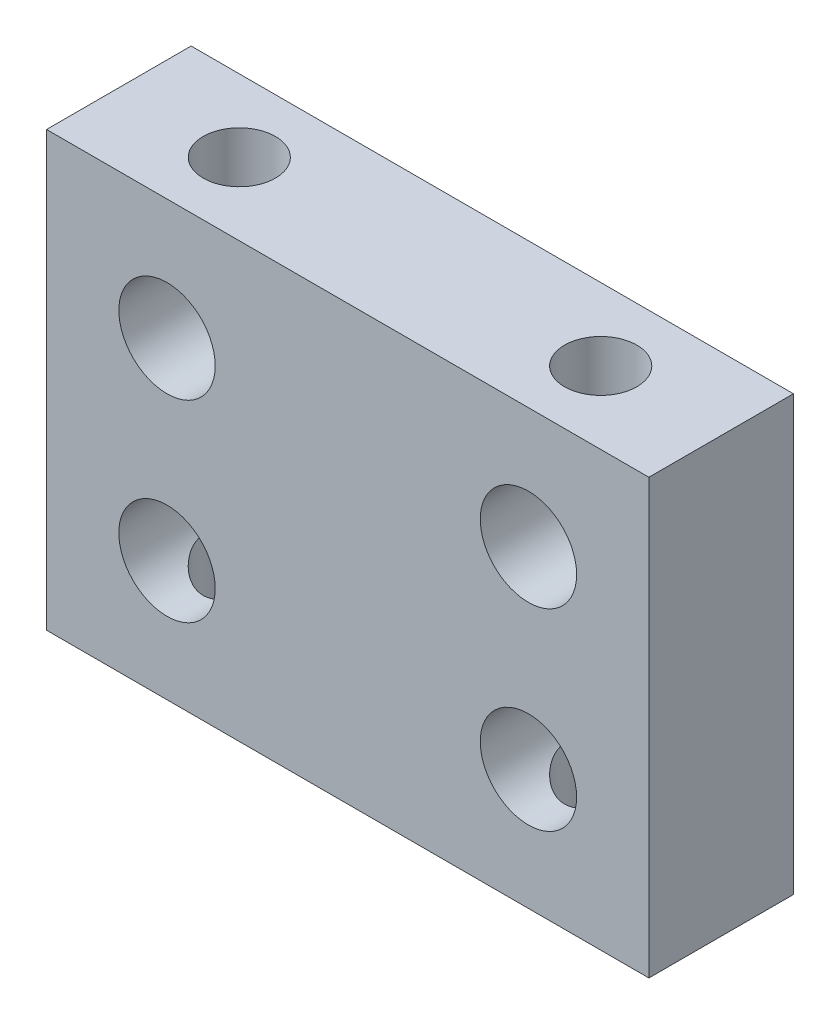
SolidWorks part; units mm, degrees
material "Beech"
ref_plane "Front Plane" through (0, 0, 0) normal (0, 0, 1) x (1, 0, 0)
ref_plane "Top Plane" through (0, 0, 0) normal (0, 1, 0) x (1, 0, 0)
ref_plane "Right Plane" through (0, 0, 0) normal (1, 0, 0) x (0, 0, -1)
sketch "Sketch1" plane through (0, 0, 0) normal (0, 0, 1) x (1, 0, 0)
  line L0 (-37.9574, 8) -> (34.5401, 8) construction
  line L1 (-25, -18) -> (25, -18)
  line L2 (-25, -18) -> (-25, 18)
  line L3 (-25, 18) -> (25, 18)
  line L4 (25, -18) -> (25, 18)
  line L5 (-25, -18) -> (25, 18) construction
  line L6 (-25, 18) -> (25, -18) construction
  line L7 (-37.9574, -8) -> (34.5401, -8) construction
  line L8 (-15, 21.2058) -> (-15, -23.6675) construction
  line L9 (15, 21.2058) -> (15, -23.6675) construction
  circle A0 centre (-15, 8) radius 4
  circle A1 centre (-15, -8) radius 4
  circle A2 centre (15, -8) radius 4
  circle A3 centre (15, 8) radius 4
  point P0 (0, 0)
  dimension "D7" = 8
  dimension "D8" = 8
  dimension "D9" = 8
  dimension "D10" = 8
  dimension "D1" = 50
  dimension "D2" = 36
  dimension "D3" = 10
  dimension "D4" = 10
  dimension "D5" = 15
  dimension "D6" = 15
extrude "Boss-Extrude1" add sketch "Sketch1" along normal blind 12
sketch "Sketch2" plane through (0, 18, 0) normal (0, 1, 0) x (1, 0, 0)
  line L0 (-22.806, -6) -> (31.3966, -6) construction
  line L2 (25, 0) -> (-25, 0) construction
  circle A0 centre (-15, -6) radius 3
  circle A1 centre (15, -6) radius 3
  point P8 (0, 0)
  point P9 (0, 0)
  dimension "D1" = 6
  dimension "D2" = 6
  dimension "D3" = 15
  dimension "D4" = 15
extrude "Cut-Extrude1" cut sketch "Sketch2" against normal up to next
mirror "Mirror1" about plane through (0, 0, 0) normal (0, 1, 0) of "Cut-Extrude1"
